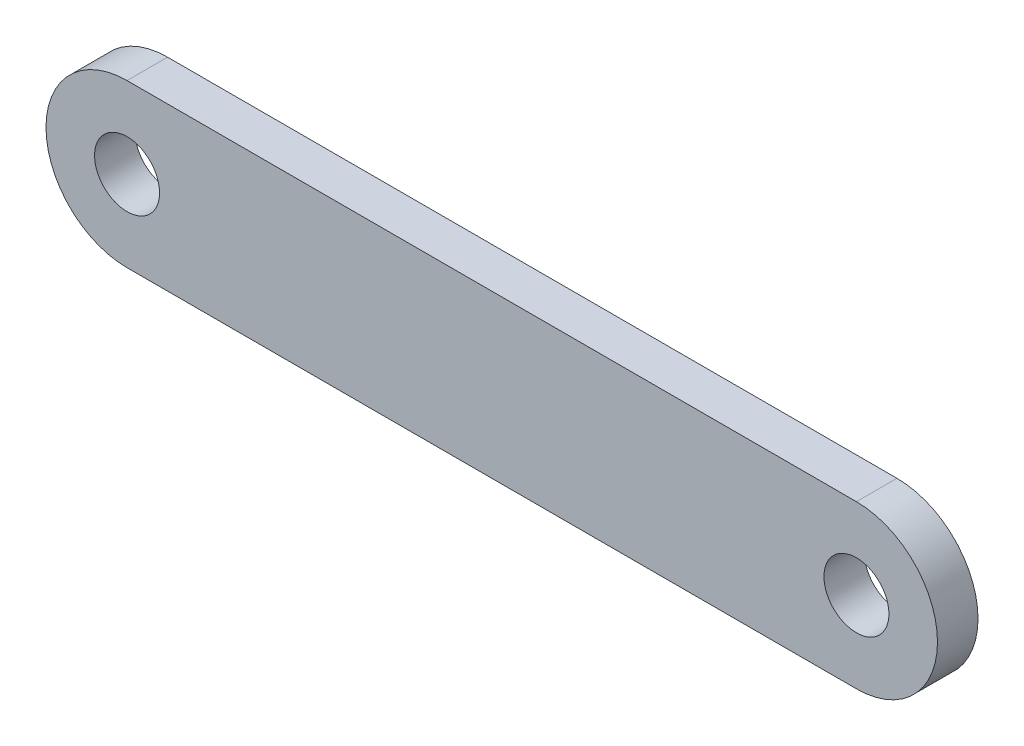
SolidWorks part; units mm, degrees
ref_plane "Front Plane" through (0, 0, 0) normal (0, 0, 1) x (1, 0, 0)
ref_plane "Top Plane" through (0, 0, 0) normal (0, 1, 0) x (1, 0, 0)
ref_plane "Right Plane" through (0, 0, 0) normal (1, 0, 0) x (0, 0, -1)
sketch "Sketch1" plane through (0, 0, 0) normal (0, 0, 1) x (1, 0, 0)
  line L0 (0, 10) -> (90, 10)
  line L1 (0, -10) -> (100, -10)
  circle A0 centre (0, 0) radius 10
  circle A1 centre (90, 0) radius 10
  dimension "D1" = 20
  dimension "D2" = 20
  dimension "D3" = 90
extrude "Boss-Extrude1" add sketch "Sketch1" along normal blind 5
sketch "Sketch2" plane through (0, 0, 5) normal (0, 0, 1) x (1, 0, 0)
  circle A0 centre (0, 0) radius 4.01
  circle A1 centre (90, 0) radius 4.01
  dimension "D1" = 8.02
  dimension "D2" = 8.02
extrude "Cut-Extrude1" cut sketch "Sketch2" against normal blind 10
